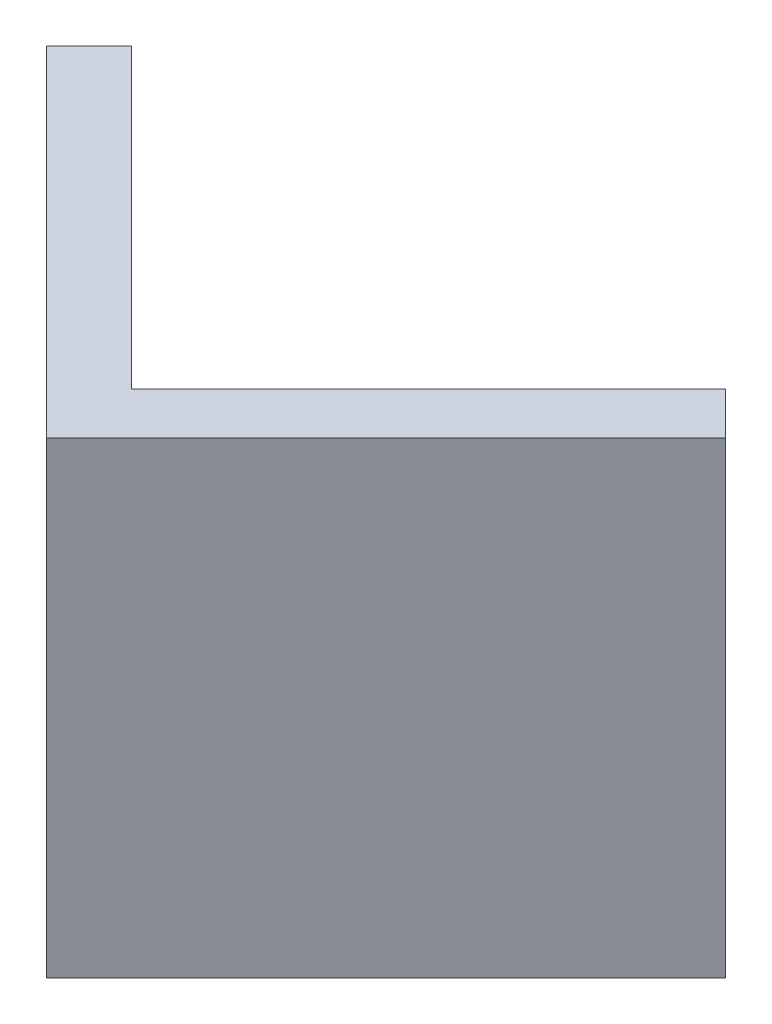
SolidWorks part; units mm, degrees
ref_plane "Alzado" through (0, 0, 0) normal (0, 0, 1) x (1, 0, 0)
ref_plane "Planta" through (0, 0, 0) normal (0, 1, 0) x (1, 0, 0)
ref_plane "Vista lateral" through (0, 0, 0) normal (1, 0, 0) x (0, 0, -1)
sketch "Croquis1" plane through (0, 0, 0) normal (0, 1, 0) x (1, 0, 0)
  line L0 (8.2843, 28.2843) -> (36.5685, 0)
  line L1 (8.2843, 28.2843) -> (-20, 0)
  line L2 (36.5685, 0) -> (8.2843, -28.2843)
  line L3 (-20, 0) -> (8.2843, -28.2843)
  line L4 (0, 0) -> (-73.3071, 0) construction
  point P7 (0, 0)
  dimension "D1" = 45
  dimension "D2" = 20
  dimension "D3" = 40
  dimension "D4" = 40
extrude "Saliente-Extruir1" add sketch "Croquis1" along normal blind 4
sketch "Croquis2" plane through (0, 4, 0) normal (0, 1, 0) x (1, 0, 0)
  line L0 (-20, 0) -> (-16.4645, 3.5355)
  line L1 (8.2843, 28.2843) -> (-20, 0) construction
  line L2 (8.2843, -21.2132) -> (33.033, 3.5355)
  line L3 (36.5685, 0) -> (8.2843, 28.2843) construction
  line L4 (33.033, 3.5355) -> (36.5685, 0)
  line L5 (36.5685, 0) -> (8.2843, -28.2843)
  line L6 (8.2843, -28.2843) -> (-20, 0)
  line L7 (-16.4645, 3.5355) -> (8.2843, -21.2132)
  point P5 (-16.4645, 3.5355)
  point P9 (0, 0)
  point P15 (0, 0)
  point P16 (0, 0)
  dimension "D1" = 5
  dimension "D2" = 5
extrude "Saliente-Extruir2" add sketch "Croquis2" along normal blind 35
